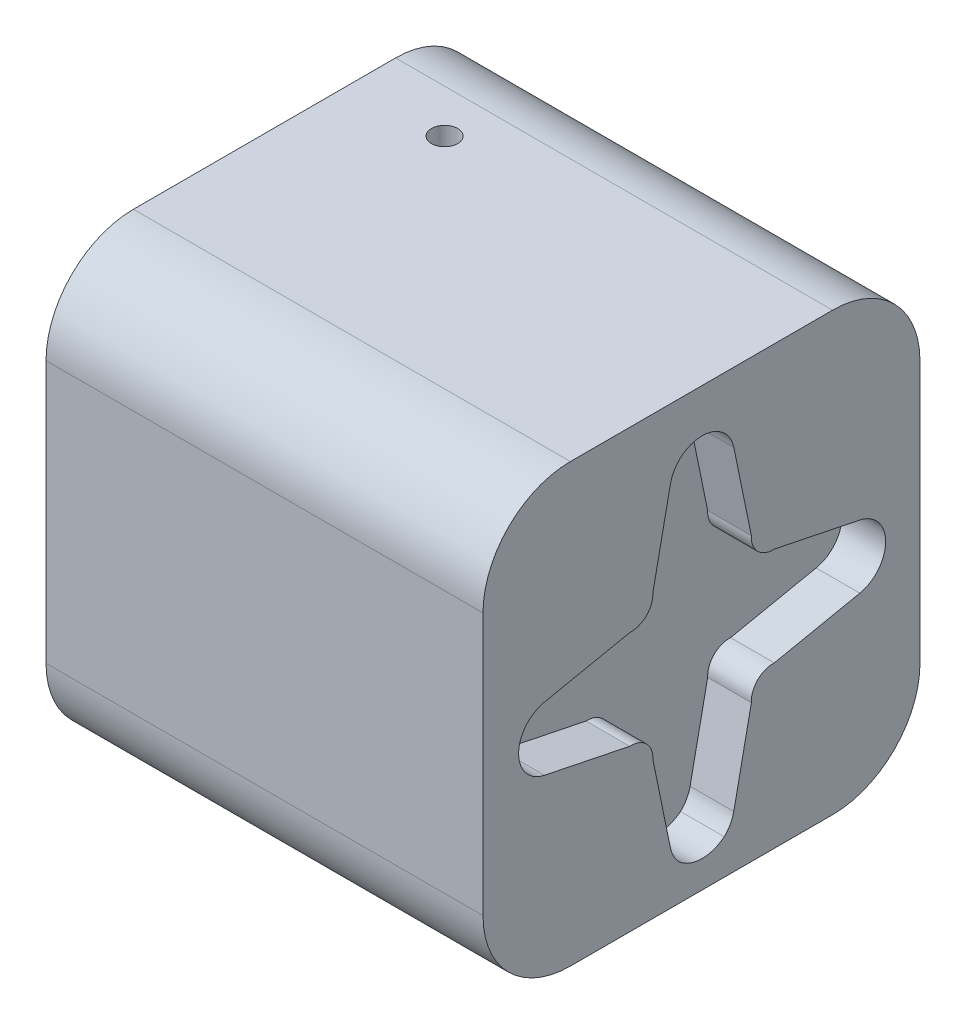
SolidWorks part; units mm, degrees
ref_plane "Plan de face" through (0, 0, 0) normal (0, 0, 1) x (1, 0, 0)
ref_plane "Plan de dessus" through (0, 0, 0) normal (0, 1, 0) x (1, 0, 0)
ref_plane "Plan de droite" through (0, 0, 0) normal (1, 0, 0) x (0, 0, -1)
sketch "Esquisse1" plane through (0, 0, 0) normal (0, 0, 1) x (1, 0, 0)
  line L1 (0, 0) -> (50, 0)
  line L2 (0, 0) -> (0, 50)
  line L3 (0, 50) -> (50, 50)
  line L4 (50, 0) -> (50, 50)
  dimension "D1" = 50
  dimension "D2" = 50
extrude "Boss.-Extru.1" add sketch "Esquisse1" along normal blind 50
sketch "Esquisse2" plane through (0, 0, 0) normal (-1, 0, 0) x (0, 0, 1)
  circle A0 centre (24.9769, 24.8563) radius 6
  point P2 (14.7724, 15.7289)
  point P3 (15.2645, 14.6767)
  dimension "D1" = 12
extrude "Enlèv. mat.-Extru.1" cut sketch "Esquisse2" against normal blind 40
fillet "Congé1" radius 10 4 edges at (25, 0, 50) (25, 50, 0) (25, 50, 50) (25, 0, 0)
sketch "Esquisse3" plane through (0, 50, 0) normal (0, 1, 0) x (1, 0, 0)
  circle A0 centre (10.5467, -14.941) radius 1.5
  dimension "D1" = 3
extrude "Enlèv. mat.-Extru.2" cut sketch "Esquisse3" against normal blind 15
sketch "Esquisse4" plane through (50, 0, 0) normal (1, 0, 0) x (0, 0, -1)
  line L0 (-24.9266, 4.0198) -> (-24.9266, 24.0198) construction
  line L1 (-33.0583, 32.1515) -> (-24.9266, 24.0198) construction
  line L2 (-20.7948, 32.1515) -> (-22.7717, 41.763) construction
  line L3 (-16.7948, 28.1515) -> (-7.1833, 26.1747) construction
  line L4 (-16.7948, 19.8881) -> (-7.1833, 21.8649) construction
  line L5 (-20.7948, 15.8881) -> (-22.7717, 6.2766) construction
  line L6 (-48.6494, 24.0198) -> (-1.2037, 24.0198) construction
  line L7 (-29.0583, 32.1515) -> (-27.0814, 41.763) construction
  line L8 (-33.0583, 28.1515) -> (-42.6698, 26.1747) construction
  line L9 (-29.0583, 15.8881) -> (-27.0814, 6.2766) construction
  line L10 (-33.0583, 19.8881) -> (-42.6698, 21.8649) construction
  line L11 (-19.2912, 32.2865) -> (-21.3024, 42.0652)
  line L12 (-30.5619, 32.2865) -> (-28.5507, 42.0652)
  line L13 (-33.1932, 29.6552) -> (-42.9719, 27.6439)
  line L14 (-33.1932, 18.3844) -> (-42.9719, 20.3957)
  line L15 (-30.5619, 15.7531) -> (-28.5507, 5.9744)
  line L16 (-19.2912, 15.7531) -> (-21.3024, 5.9744)
  line L17 (-16.6599, 18.3844) -> (-6.8812, 20.3957)
  line L18 (-16.6599, 29.6552) -> (-6.8812, 27.6439)
  arc A0 (-22.7717, 41.763) -> (-27.0814, 41.763) centre (-24.9266, 41.3198) ccw construction
  arc A1 (-42.6698, 26.1747) -> (-42.6698, 21.8649) centre (-42.2266, 24.0198) ccw construction
  arc A2 (-33.0583, 28.1515) -> (-29.0583, 32.1515) centre (-33.0583, 32.1515) ccw construction
  arc A3 (-16.7948, 28.1515) -> (-20.7948, 32.1515) centre (-16.7948, 32.1515) cw construction
  arc A4 (-7.1833, 26.1747) -> (-7.1833, 21.8649) centre (-7.6266, 24.0198) cw construction
  arc A5 (-22.7717, 6.2766) -> (-27.0814, 6.2766) centre (-24.9266, 6.7198) cw construction
  arc A6 (-16.7948, 19.8881) -> (-20.7948, 15.8881) centre (-16.7948, 15.8881) ccw construction
  arc A7 (-33.0583, 19.8881) -> (-29.0583, 15.8881) centre (-33.0583, 15.8881) cw construction
  arc A8 (-21.3024, 42.0652) -> (-28.5507, 42.0652) centre (-24.9266, 41.3198) ccw
  arc A9 (-33.1932, 29.6552) -> (-30.5619, 32.2865) centre (-33.0583, 32.1515) ccw
  arc A10 (-42.9719, 27.6439) -> (-42.9719, 20.3957) centre (-42.2266, 24.0198) ccw
  arc A11 (-33.1932, 18.3844) -> (-30.5619, 15.7531) centre (-33.0583, 15.8881) cw
  arc A12 (-21.3024, 5.9744) -> (-22.3967, 4.0198) centre (-24.9266, 6.7198) cw
  arc A13 (-16.6599, 18.3844) -> (-19.2912, 15.7531) centre (-16.7948, 15.8881) ccw
  arc A14 (-6.8812, 27.6439) -> (-6.8812, 20.3957) centre (-7.6266, 24.0198) cw
  arc A15 (-16.6599, 29.6552) -> (-19.2912, 32.2865) centre (-16.7948, 32.1515) cw
  arc A16 (-27.4564, 4.0198) -> (-28.5507, 5.9744) centre (-24.9266, 6.7198) cw
  arc A17 (-22.3967, 4.0198) -> (-27.4564, 4.0198) centre (-24.9266, 7.1414) cw
  point P6 (-44.4266, 24.0198)
  point P20 (-24.9266, 43.5198)
  point P32 (-30.2299, 29.3231)
  point P57 (0, 0)
  point P58 (0, 0)
  point P61 (-21.3024, 4.0198)
  point P62 (-27.4564, 3.2916)
  dimension "D2" = 2.2
  dimension "D3" = 2.2
  dimension "D7" = 4
  dimension "D1" = 20
  dimension "D4" = 19.5
  dimension "D5" = 19.5
  dimension "D6" = 7.5
extrude "Enlèv. mat.-Extru.3" cut sketch "Esquisse4" against normal blind 5
